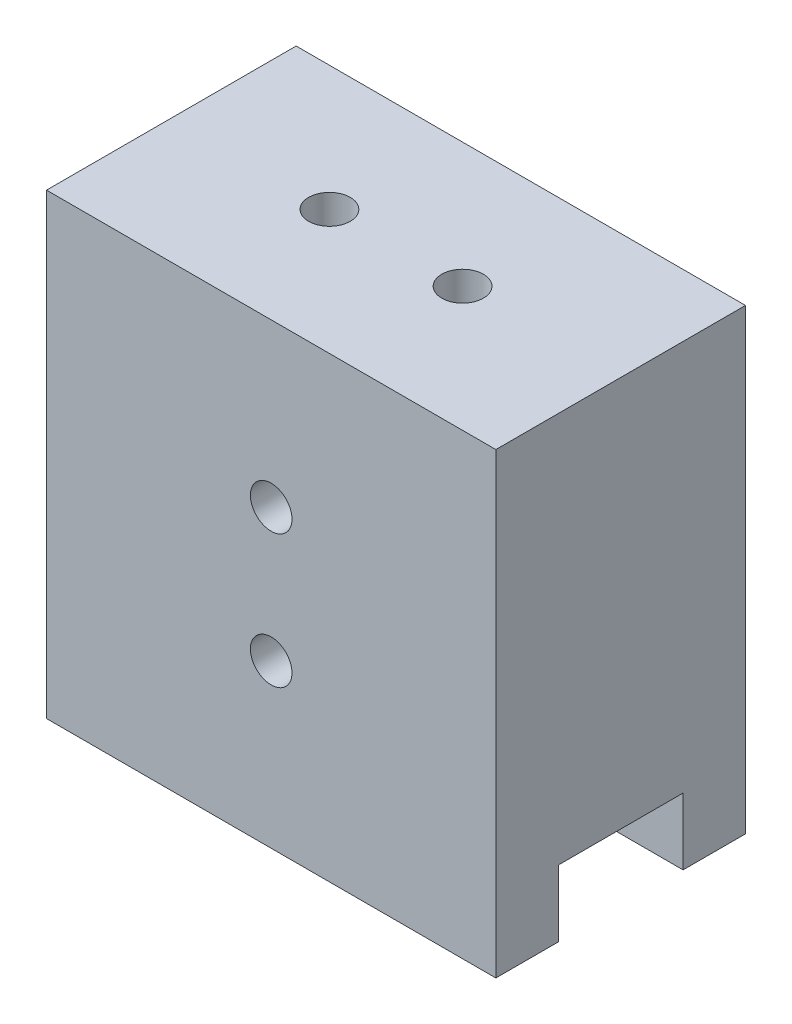
SolidWorks part; units mm, degrees
ref_plane "Front Plane" through (0, 0, 0) normal (0, 0, 1) x (1, 0, 0)
ref_plane "Top Plane" through (0, 0, 0) normal (0, 1, 0) x (1, 0, 0)
ref_plane "Right Plane" through (0, 0, 0) normal (1, 0, 0) x (0, 0, -1)
sketch "Sketch1" plane through (0, 0, 0) normal (0, 0, 1) x (1, 0, 0)
  line L1 (0, 0) -> (54, 0)
  line L2 (0, 0) -> (0, 55)
  line L3 (0, 55) -> (54, 55)
  line L4 (54, 0) -> (54, 55)
  dimension "D1" = 54
  dimension "D2" = 55
extrude "Boss-Extrude1" add sketch "Sketch1" along normal blind 30
sketch "Sketch2" plane through (0, 0, 0) normal (0, -1, 0) x (1, 0, 0)
  line L0 (0, 30) -> (54, 30) construction
  line L1 (0, 22.5) -> (54, 22.5)
  line L2 (0, 22.5) -> (0, 7.5)
  line L3 (0, 7.5) -> (54, 7.5)
  line L4 (54, 22.5) -> (54, 7.5)
  line L5 (54, 30) -> (54, 0) construction
  point P0 (27, 15)
  dimension "D1" = 54
  dimension "D2" = 15
  dimension "D3" = 7.5
extrude "Cut-Extrude1" cut sketch "Sketch2" against normal blind 8
sketch "Sketch3" plane through (0, 55, 0) normal (0, 1, 0) x (1, 0, 0)
  circle A0 centre (19, -15) radius 2.5
  circle A1 centre (35, -15) radius 2.5
  dimension "D1" = 5
  dimension "D2" = 16
extrude "Cut-Extrude2" cut sketch "Sketch3" against normal blind 10
sketch "Sketch4" plane through (0, 0, 30) normal (0, 0, 1) x (1, 0, 0)
  circle A0 centre (27, 35.5) radius 2.5
  circle A1 centre (27, 19.5) radius 2.5
  dimension "D1" = 5
  dimension "D2" = 16
extrude "Cut-Extrude3" cut sketch "Sketch4" against normal blind 10
